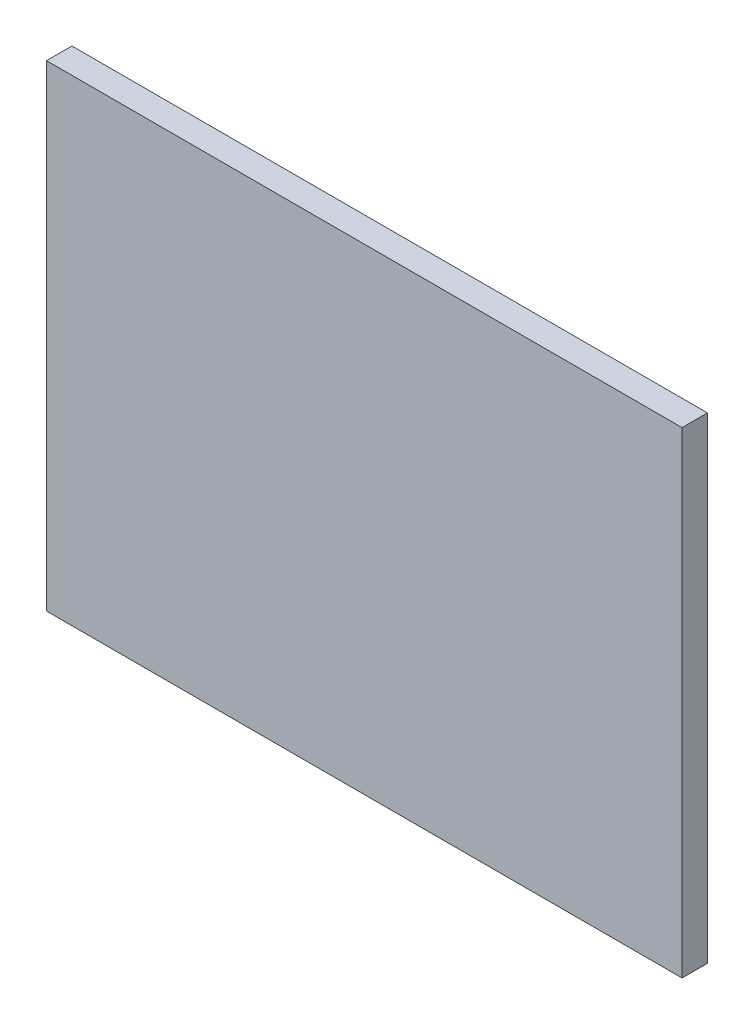
SolidWorks part; units mm, degrees
ref_plane "Plan de face" through (0, 0, 0) normal (0, 0, 1) x (1, 0, 0)
ref_plane "Plan de dessus" through (0, 0, 0) normal (0, 1, 0) x (1, 0, 0)
ref_plane "Plan de droite" through (0, 0, 0) normal (1, 0, 0) x (0, 0, -1)
sketch "Esquisse2" plane through (0, 0, 0) normal (0, 0, 1) x (1, 0, 0)
  line L1 (80, 60) -> (0, 60)
  line L2 (80, 60) -> (80, 0)
  line L3 (80, 0) -> (0, 0)
  line L4 (0, 60) -> (0, 0)
  dimension "D1" = 80
  dimension "D2" = 60
extrude "Boss.-Extru.1" add sketch "Esquisse2" along normal blind 3.2
